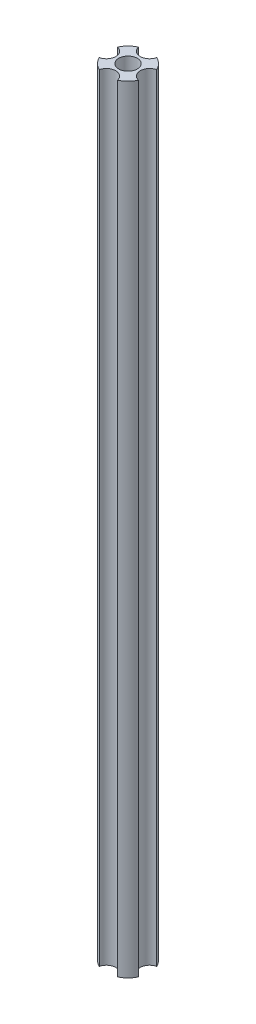
SolidWorks part; units mm, degrees
ref_plane "Front Plane" through (0, 0, 0) normal (0, 0, 1) x (1, 0, 0)
ref_plane "Top Plane" through (0, 0, 0) normal (0, 1, 0) x (1, 0, 0)
ref_plane "Right Plane" through (0, 0, 0) normal (1, 0, 0) x (0, 0, -1)
sketch "Sketch1" plane through (0, 0, 0) normal (0, 1, 0) x (1, 0, 0)
  circle A0 centre (0, 0) radius 1.5
  arc A1 (-3.1513, -1.4646) -> (-1.4646, -3.1513) centre (0, 0) ccw
  arc A2 (-1.4646, 3.1513) -> (1.4646, 3.1513) centre (0, 3.475) ccw
  arc A3 (3.1513, 1.4646) -> (3.1513, -1.4646) centre (3.475, 0) ccw
  arc A4 (1.4646, -3.1513) -> (-1.4646, -3.1513) centre (0, -3.475) ccw
  arc A5 (-3.1513, -1.4646) -> (-3.1513, 1.4646) centre (-3.475, 0) ccw
  arc A6 (1.4646, 3.1513) -> (-1.4646, 3.1513) centre (0, 3.475) ccw construction
  arc A7 (-3.1513, 1.4646) -> (-3.1513, -1.4646) centre (-3.475, 0) ccw construction
  arc A8 (-1.4646, -3.1513) -> (1.4646, -3.1513) centre (0, -3.475) ccw construction
  arc A9 (3.1513, -1.4646) -> (3.1513, 1.4646) centre (3.475, 0) ccw construction
  arc A10 (-3.1513, 1.4646) -> (-3.1513, -1.4646) centre (0, 0) ccw construction
  arc A11 (-1.4646, -3.1513) -> (1.4646, -3.1513) centre (0, 0) ccw construction
  arc A12 (1.4646, -3.1513) -> (3.1513, -1.4646) centre (0, 0) ccw
  arc A13 (3.1513, -1.4646) -> (3.1513, 1.4646) centre (0, 0) ccw construction
  arc A14 (3.1513, 1.4646) -> (1.4646, 3.1513) centre (0, 0) ccw
  arc A15 (1.4646, 3.1513) -> (-1.4646, 3.1513) centre (0, 0) ccw construction
  arc A16 (-1.4646, 3.1513) -> (-3.1513, 1.4646) centre (0, 0) ccw
  dimension "D1" = 3
  dimension "D2" = 6.95
  dimension "D3" = 3
  dimension "D4" = 3
  dimension "D5" = 3
  dimension "D6" = 3
extrude "Boss-Extrude1" add sketch "Sketch1" along normal blind 125
equation "\"D4@Sketch1\"=\"D3@Sketch1\""
equation "\"D5@Sketch1\"=\"D3@Sketch1\""
equation "\"D6@Sketch1\"=\"D3@Sketch1\""
